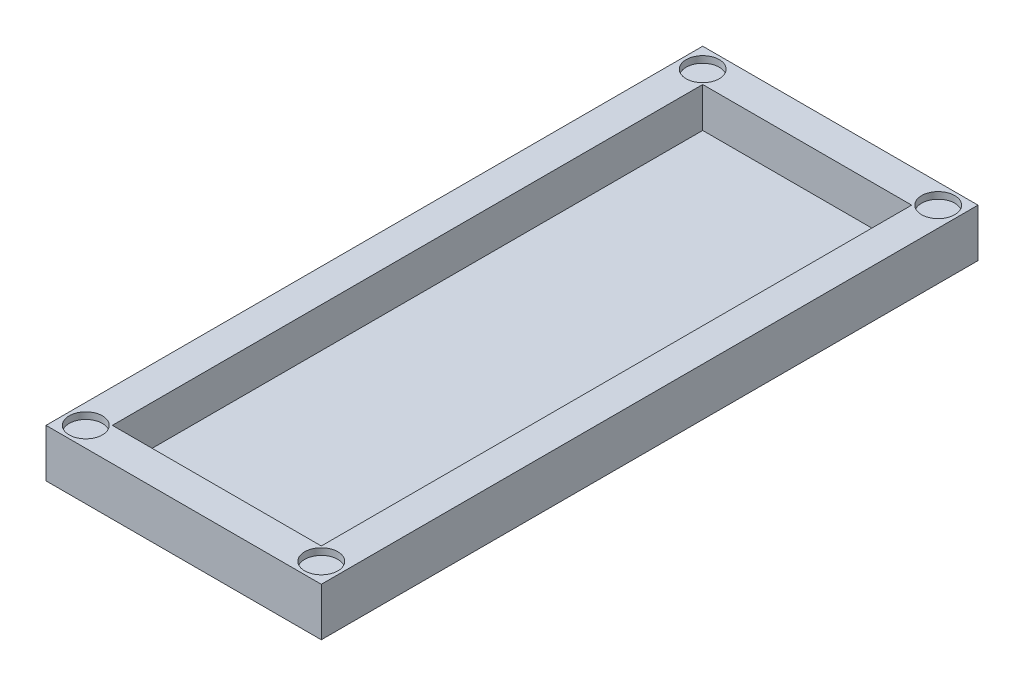
SolidWorks part; units mm, degrees
ref_plane "Front Plane" through (0, 0, 0) normal (0, 0, 1) x (1, 0, 0)
ref_plane "Top Plane" through (0, 0, 0) normal (0, 1, 0) x (1, 0, 0)
ref_plane "Right Plane" through (0, 0, 0) normal (1, 0, 0) x (0, 0, -1)
sketch "Sketch2" plane through (0, 0, 0) normal (0, 1, 0) x (1, 0, 0)
  line L1 (41.5, 99) -> (-41.5, 99)
  line L2 (41.5, 99) -> (41.5, -99)
  line L3 (41.5, -99) -> (-41.5, -99)
  line L4 (-41.5, 99) -> (-41.5, -99)
  line L5 (41.5, 99) -> (-41.5, -99) construction
  line L6 (41.5, -99) -> (-41.5, 99) construction
  point P0 (0, 0)
  dimension "D1" = 198
  dimension "D2" = 83
extrude "Boss-Extrude5" add sketch "Sketch2" along normal blind 2.5
sketch "Sketch5" plane through (0, 2.5, 0) normal (0, 1, 0) x (1, 0, 0)
  line L1 (41.5, 99) -> (-41.5, 99)
  line L2 (41.5, 99) -> (41.5, -99)
  line L3 (41.5, -99) -> (-41.5, -99)
  line L4 (-41.5, 99) -> (-41.5, -99)
  line L5 (41.5, 99) -> (-41.5, -99) construction
  line L6 (41.5, -99) -> (-41.5, 99) construction
  line L7 (31.5, 89) -> (-31.5, 89)
  line L8 (31.5, 89) -> (31.5, -89)
  line L9 (31.5, -89) -> (-31.5, -89)
  line L10 (-31.5, 89) -> (-31.5, -89)
  line L11 (31.5, 89) -> (-31.5, -89) construction
  line L12 (31.5, -89) -> (-31.5, 89) construction
  point P0 (0, 0)
  point P7 (0, 0)
  dimension "D1" = 178
  dimension "D2" = 63
extrude "Boss-Extrude6" add sketch "Sketch5" along normal blind 12
sketch "Sketch6" plane through (0, 14.5, 0) normal (0, 1, 0) x (1, 0, 0)
  line L0 (-41.5, -99) -> (41.5, -99) construction
  line L1 (-41.5, 99) -> (-41.5, -99) construction
  line L3 (41.5, 99) -> (-41.5, 99) construction
  line L4 (41.5, -99) -> (41.5, 99) construction
  circle A0 centre (-35.5, -93) radius 5
  circle A1 centre (35.5, -93) radius 5
  circle A2 centre (35.5, 93) radius 5
  circle A3 centre (-35.5, 93) radius 5
  point P12 (0, 0)
  point P19 (0, 0)
  point P21 (59.4059, -79.6802)
  dimension "D1" = 10
  dimension "D2" = 6
  dimension "D3" = 6
  dimension "D6" = 6
  dimension "D7" = 6
  dimension "D8" = 6
  dimension "D4" = 2
  dimension "D5" = 2
extrude "Cut-Extrude1" cut sketch "Sketch6" against normal blind 2
sketch "Sketch9" plane through (0, 0, 0) normal (0, -1, 0) x (-1, 0, 0)
  text T0 "COW-A-BUNGA" font "Cooper Black" height 3.5
extrude "Cut-Extrude2" cut sketch "Sketch9" against normal blind 1
